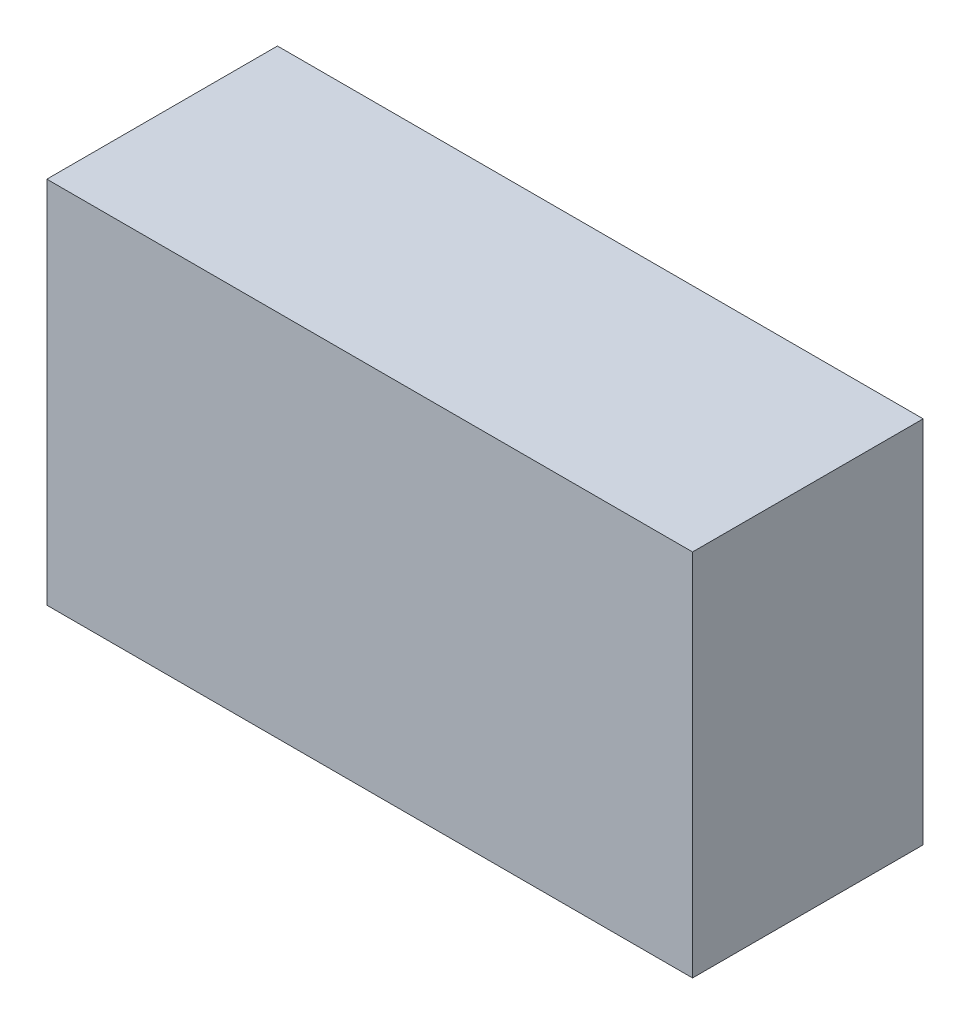
SolidWorks part; units mm, degrees
ref_plane "Front Plane" through (0, 0, 0) normal (0, 0, 1) x (1, 0, 0)
ref_plane "Top Plane" through (0, 0, 0) normal (0, 1, 0) x (1, 0, 0)
ref_plane "Right Plane" through (0, 0, 0) normal (1, 0, 0) x (0, 0, -1)
other "Configuration Table"
sketch "Sketch1" plane through (0, 0, 0) normal (0, 0, 1) x (1, 0, 0)
  line L1 (280, 1174) -> (420, 1174)
  line L2 (280, 1174) -> (280, 1254)
  line L3 (280, 1254) -> (420, 1254)
  line L4 (420, 1174) -> (420, 1254)
extrude "PRESS_uc_catal_sirt_1" add sketch "Sketch1" against normal blind 50 from offset 550 separate body
